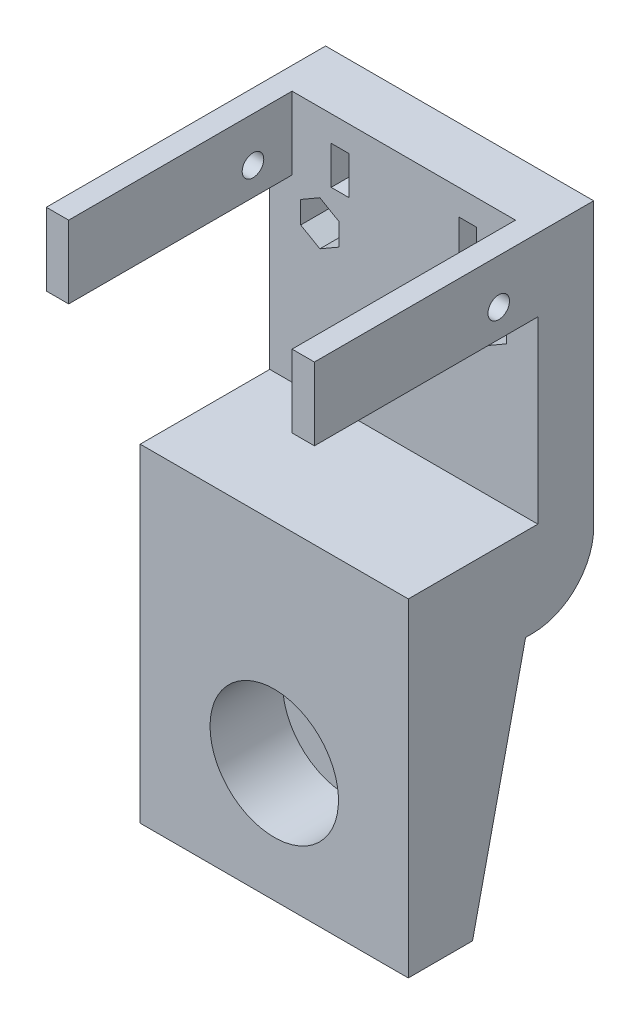
SolidWorks part; units mm, degrees
ref_plane "Front Plane" through (0, 0, 0) normal (0, 0, 1) x (1, 0, 0)
ref_plane "Top Plane" through (0, 0, 0) normal (0, 1, 0) x (1, 0, 0)
ref_plane "Right Plane" through (0, 0, 0) normal (1, 0, 0) x (0, 0, -1)
sketch "Sketch1" plane through (0, 0, 0) normal (0, 0, 1) x (1, 0, 0)
  line L1 (0, 0) -> (48, 0)
  line L2 (0, 0) -> (0, 53)
  line L3 (0, 53) -> (48, 53)
  line L4 (48, 0) -> (48, 53)
  circle A0 centre (8.975, 38) radius 1.9304
  circle A1 centre (38.975, 38) radius 1.9304
  dimension "D1" = 53
  dimension "D2" = 48
extrude "Boss-Extrude1" add sketch "Sketch1" along normal blind 10
sketch "Sketch2" plane through (0, 0, 0) normal (0, 0, -1) x (-1, 0, 0)
  line L0 (0, 53) -> (0, 0) construction
  line L1 (-48, 0) -> (0, 0)
  line L2 (-48, 0) -> (-48, -5.6163)
  line L3 (-48, -5.6163) -> (0, -5.6163)
  line L4 (0, 0) -> (0, -5.6163)
  dimension "D1" = 5.6163
extrude "Boss-Extrude2" add sketch "Sketch2" against normal blind 33.1918
sketch "Sketch4" plane through (0, 0, 10) normal (0, 0, 1) x (1, 0, 0)
  line L1 (0, 53) -> (4, 53)
  line L2 (0, 53) -> (0, 43)
  line L3 (0, 43) -> (4, 43)
  line L4 (4, 53) -> (4, 43)
  line L5 (48, 53) -> (44, 53)
  line L6 (48, 53) -> (48, 43)
  line L7 (48, 43) -> (44, 43)
  line L8 (44, 53) -> (44, 43)
  dimension "D1" = 10
  dimension "D2" = 4
extrude "Boss-Extrude4" add sketch "Sketch4" along normal blind 40
sketch "Sketch5" plane through (0, 0, 10) normal (0, 0, 1) x (1, 0, 0)
  line L0 (48, 0) -> (48, 43) construction
  line L1 (0, 0) -> (48, 0)
  line L2 (0, 0) -> (0, 10.8609)
  line L3 (0, 10.8609) -> (48, 10.8609)
  line L4 (48, 0) -> (48, 10.8609)
  dimension "D1" = 10.8609
extrude "Boss-Extrude5" add sketch "Sketch5" along normal up to surface (23.1918 mm away) up to face at (24, -2.8082, 33.1918)
sketch "Sketch6" plane through (0, -5.6163, 0) normal (0, -1, 0) x (1, 0, 0)
  line L0 (0, 0) -> (0, 28.1918) construction
  line L1 (0, 33.1918) -> (0, 0) construction
  line L2 (48, 33.1918) -> (48, 0) construction
  line L3 (0, 28.1918) -> (48, 28.1918)
  line L4 (0, 28.1918) -> (0, 33.1918)
  line L5 (0, 33.1918) -> (48, 33.1918)
  line L6 (48, 28.1918) -> (48, 33.1918)
  line L8 (48, 33.1918) -> (0, 33.1918) construction
  dimension "D2" = 5
extrude "Boss-Extrude6" add sketch "Sketch6" along normal blind 42.3
sketch "Sketch8" plane through (0, 0, 28.1918) normal (0, 0, -1) x (-1, 0, 0)
  line L0 (-24, -26.6163) -> (-24, -5.6163) construction
  line L1 (0, -5.6163) -> (-48, -5.6163) construction
  line L3 (-8.5, -42.1163) -> (-39.5, -42.1163) construction
  line L4 (-8.5, -42.1163) -> (-8.5, -11.1163) construction
  line L5 (-8.5, -11.1163) -> (-39.5, -11.1163) construction
  line L6 (-39.5, -42.1163) -> (-39.5, -11.1163) construction
  line L7 (-8.5, -42.1163) -> (-39.5, -11.1163) construction
  line L8 (-8.5, -11.1163) -> (-39.5, -42.1163) construction
  circle A0 centre (-24, -26.6163) radius 11.5
  circle A1 centre (-39.5, -11.1163) radius 2 construction
  circle A2 centre (-39.5, -42.1163) radius 2 construction
  circle A3 centre (-8.5, -11.1163) radius 2 construction
  circle A4 centre (-8.5, -42.1163) radius 2 construction
  dimension "D2" = 23
  dimension "D4" = 4
  dimension "D1" = 21
  dimension "D3" = 31
extrude "Cut-Extrude1" cut sketch "Sketch8" against normal up to next
sketch "Sketch9" plane through (48, 0, 0) normal (1, 0, 0) x (0, 0, -1)
  line L0 (0, -5.6163) -> (0, 53) construction
  line L1 (-50, 43) -> (-17, 48) construction
  line L2 (-17, 48) -> (-50, 53) construction
  circle A0 centre (-17, 48) radius 1.9304
  dimension "D1" = 3.8608
  dimension "D2" = 17
extrude "Cut-Extrude2" cut sketch "Sketch9" against normal through all
sketch "Sketch10" plane through (0, 0, 0) normal (0, 0, -1) x (-1, 0, 0)
  line L0 (-48, 53) -> (-37, 51.4163) construction
  line L1 (-37, 51.4163) -> (-33.8453, 51.4163)
  line L2 (-37, 51.4163) -> (-37, 44.5837)
  line L3 (-37, 44.5837) -> (-33.8453, 44.5837)
  line L4 (-33.8453, 51.4163) -> (-33.8453, 44.5837)
  line L5 (-14.1547, 51.4163) -> (-11, 51.4163)
  line L6 (-14.1547, 51.4163) -> (-14.1547, 44.5837)
  line L7 (-14.1547, 44.5837) -> (-11, 44.5837)
  line L8 (-11, 51.4163) -> (-11, 44.5837)
  line L9 (0, 53) -> (-11, 51.4163) construction
  line L10 (-48, 53) -> (0, 53) construction
  dimension "D1" = 3.1547
  dimension "D2" = 1.5837
  dimension "D3" = 6.8326
  dimension "D4" = 19.6906
extrude "Cut-Extrude3" cut sketch "Sketch10" against normal up to next
sketch "Sketch11" plane through (0, 0, 28.1918) normal (0, 0, -1) x (-1, 0, 0)
  line L1 (-48, -5.6163) -> (0, -5.6163)
  line L2 (-48, -5.6163) -> (-48, -47.9163)
  line L3 (-48, -47.9163) -> (0, -47.9163)
  line L4 (0, -5.6163) -> (0, -47.9163)
  circle A0 centre (-24, -26.6163) radius 11.5
  circle A1 centre (-24, -26.6163) radius 11.5 construction
extrude "Boss-Extrude7" add sketch "Sketch11" along normal blind 8
sketch "Sketch12" plane through (0, 0, 20.1918) normal (0, 0, -1) x (-1, 0, 0)
  line L1 (-48, -5.6163) -> (0, -5.6163)
  line L2 (-48, -5.6163) -> (-48, -47.9163)
  line L3 (-48, -47.9163) -> (0, -47.9163)
  line L4 (0, -5.6163) -> (0, -47.9163)
extrude "Boss-Extrude8" add sketch "Sketch12" along normal blind 8
fillet "Fillet1" radius 11 1 edges at (24, -5.6163, 0)
sketch "Sketch13" plane through (0, 53, 0) normal (0, 1, 0) x (1, 0, 0)
  line L0 (0, 0) -> (0, -50)
  line L1 (0, -50) -> (4, -50)
  line L2 (4, -50) -> (4, -10)
  line L3 (4, -10) -> (44, -10)
  line L4 (44, -10) -> (44, -50)
  line L5 (44, -50) -> (48, -50)
  line L6 (48, -50) -> (48, 0)
  line L7 (48, 0) -> (0, 0)
extrude "Boss-Extrude9" add sketch "Sketch13" along normal blind 3
sketch "Sketch14" plane through (0, 0, 10) normal (0, 0, 1) x (1, 0, 0)
  line L1 (8.975, 41.9595) -> (5.546, 39.9797)
  line L2 (5.546, 39.9797) -> (5.546, 36.0203)
  line L3 (5.546, 36.0203) -> (8.975, 34.0405)
  line L4 (8.975, 34.0405) -> (12.404, 36.0203)
  line L5 (12.404, 36.0203) -> (12.404, 39.9797)
  line L6 (12.404, 39.9797) -> (8.975, 41.9595)
  line L7 (38.975, 41.9595) -> (35.546, 39.9797)
  line L8 (35.546, 39.9797) -> (35.546, 36.0203)
  line L9 (35.546, 36.0203) -> (38.975, 34.0405)
  line L10 (38.975, 34.0405) -> (42.404, 36.0203)
  line L11 (42.404, 36.0203) -> (42.404, 39.9797)
  line L12 (42.404, 39.9797) -> (38.975, 41.9595)
  circle A0 centre (8.975, 38) radius 3.429 construction
  circle A1 centre (38.975, 38) radius 3.429 construction
  dimension "D1" = 3.9595
extrude "Cut-Extrude4" cut sketch "Sketch14" against normal blind 6
sketch "Sketch15" plane through (48, 0, 0) normal (1, 0, 0) x (0, 0, -1)
  line L0 (-12.1918, -5.6163) -> (-21.6917, -47.9163)
  line L1 (-12.1918, -47.9163) -> (-33.1918, -47.9163) construction
  line L2 (-21.6917, -47.9163) -> (-12.1918, -47.9163)
  line L3 (-12.1918, -47.9163) -> (-12.1918, -5.6163)
extrude "Cut-Extrude5" cut sketch "Sketch15" against normal through all
